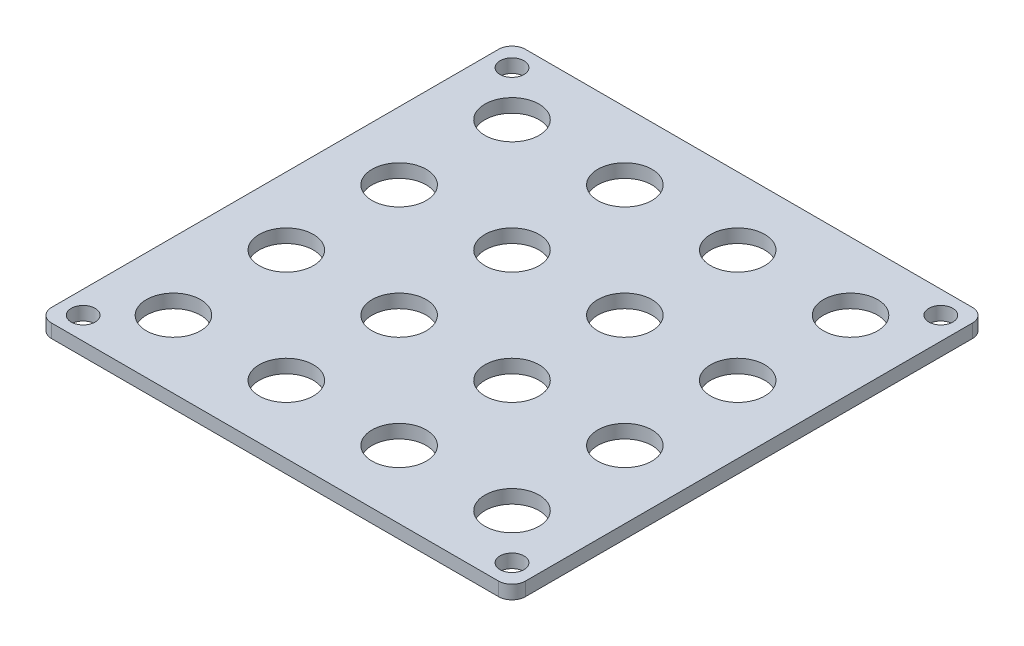
SolidWorks part; units mm, degrees
material "6061-T6 (SS)"
ref_plane "Front Plane" through (0, 0, 0) normal (0, 0, 1) x (1, 0, 0)
ref_plane "Top Plane" through (0, 0, 0) normal (0, 1, 0) x (1, 0, 0)
ref_plane "Right Plane" through (0, 0, 0) normal (1, 0, 0) x (0, 0, -1)
sketch "Sketch1" plane through (0, 0, 0) normal (0, 1, 0) x (1, 0, 0)
  line L0 (25, 0) -> (0, 0) construction
  line L1 (0, 0) -> (0, -25) construction
  line L2 (0, -50) -> (0, -75) construction
  line L3 (0, -75) -> (75, -75) construction
  line L9 (75, -75) -> (75, -50) construction
  line L10 (25, -25) -> (50, -50) construction
  line L12 (90, -90) -> (-15, -90)
  line L13 (90, -90) -> (90, 15)
  line L14 (90, 15) -> (-15, 15)
  line L15 (-15, -90) -> (-15, 15)
  line L16 (90, -90) -> (-15, 15) construction
  line L17 (90, 15) -> (-15, -90) construction
  circle A0 centre (0, 0) radius 6
  circle A1 centre (25, 0) radius 6
  circle A2 centre (50, 0) radius 6
  circle A3 centre (75, 0) radius 6
  circle A4 centre (25, -25) radius 6
  circle A5 centre (50, -25) radius 6
  circle A6 centre (75, -25) radius 6
  circle A7 centre (25, -50) radius 6
  circle A8 centre (50, -50) radius 6
  circle A9 centre (75, -50) radius 6
  circle A10 centre (0, -25) radius 6
  circle A11 centre (0, -50) radius 6
  circle A12 centre (0, -75) radius 6
  circle A14 centre (75, -75) radius 6
  circle A15 centre (25, -75) radius 6
  circle A16 centre (50, -75) radius 6
  point P31 (37.5, -37.5)
  point P38 (0, 0)
  point P39 (0, 0)
  dimension "D1" = 12
  dimension "D4" = 25
  dimension "D6" = 15
  dimension "D7" = 15
  dimension "D2" = 4
  dimension "D3" = 3
extrude "Boss-Extrude1" add sketch "Sketch1" along normal blind 3
sketch "Screw Positions" plane through (0, 3, 0) normal (0, 1, 0) x (1, 0, 0)
  line L0 (25, -25) -> (50, -50) construction
  line L2 (85, -85) -> (-10, -85)
  line L3 (85, -85) -> (85, 10)
  line L4 (85, 10) -> (-10, 10)
  line L5 (-10, -85) -> (-10, 10)
  line L6 (85, -85) -> (-10, 10) construction
  line L7 (85, 10) -> (-10, -85) construction
  line L9 (90, 15) -> (-15, 15) construction
  line L10 (-15, 15) -> (-15, -90) construction
  point P4 (37.5, -37.5)
  point P15 (37.5, -37.5)
  dimension "D1" = 5
  dimension "D2" = 5
hole_wizard "M5 Clearance Hole1" positions "Sketch3" profile "Sketch4" hole size "M5" standard "ANSI Metric" end condition up to next
sketch "Sketch3" plane through (0, 3, 0) normal (0, 1, 0) x (1, 0, 0)
  point P0 (-10, 10)
  point P3 (-10, -85)
  point P6 (85, -85)
  point P9 (85, 10)
sketch "Sketch4" plane through (-10, 3, -10) normal (1, 0, 0) x (0, 0, 1)
  line L0 (0, 0) -> (0, 3)
  line L1 (0, 3) -> (2.65, 3)
  line L2 (2.65, 3) -> (2.65, 0)
  line L5 (2.65, 0) -> (0, 0)
  line L11 (0, -6.35) -> (0, 107.95) construction
  dimension "Thru Hole Dia." = 5.3
  dimension "Thru Hole Depth" = 3
fillet "Fillet2" radius 3 4 edges at (-15, 1.5, -15) (90, 1.5, -15) (90, 1.5, 90) (-15, 1.5, 90)
